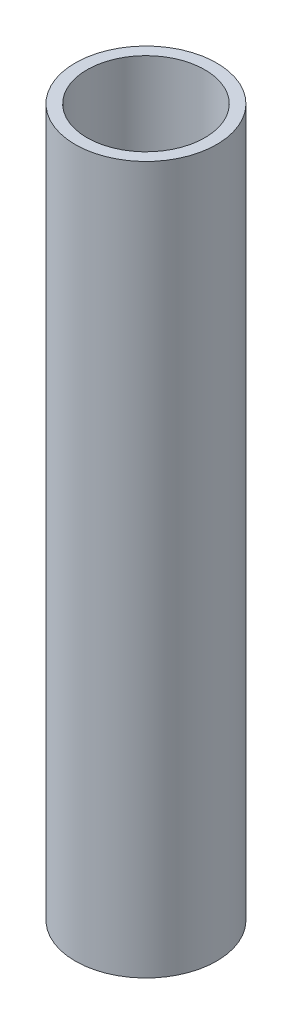
SolidWorks part; units mm, degrees
ref_plane "Спереди" through (0, 0, 0) normal (0, 0, 1) x (1, 0, 0)
ref_plane "Сверху" through (0, 0, 0) normal (0, 1, 0) x (1, 0, 0)
ref_plane "Справа" through (0, 0, 0) normal (1, 0, 0) x (0, 0, -1)
sketch "Эскиз1" plane through (0, 0, 0) normal (0, 1, 0) x (1, 0, 0)
  circle A0 centre (0, 0) radius 3
  dimension "D1" = 6
extrude "Бобышка-Вытянуть1" add sketch "Эскиз1" along normal blind 30
sketch "Эскиз2" plane through (0, 30, 0) normal (0, 1, 0) x (1, 0, 0)
  circle A0 centre (0, 0) radius 2.5
  dimension "D1" = 5
extrude "Вырез-Вытянуть1" cut sketch "Эскиз2" against normal blind 30
